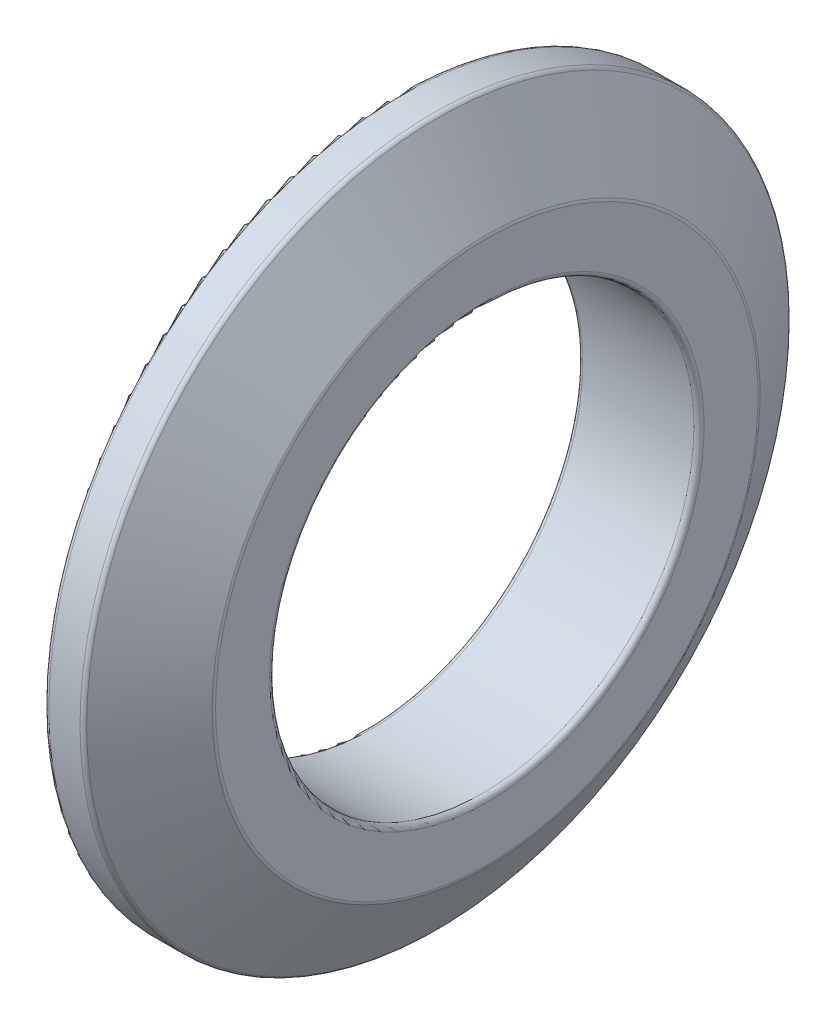
SolidWorks part; units mm, degrees
ref_plane "Front Plane" through (0, 0, 0) normal (0, 0, 1) x (1, 0, 0)
ref_plane "Top Plane" through (0, 0, 0) normal (0, 1, 0) x (1, 0, 0)
ref_plane "Right Plane" through (0, 0, 0) normal (1, 0, 0) x (0, 0, -1)
sketch "Sketch1" plane through (0, 0, 0) normal (0, 0, 1) x (1, 0, 0)
  line L0 (6, 10.75) -> (6, 13.4283)
  line L1 (0, 0) -> (6, 0) construction
  line L2 (0, 0) -> (0, 10.5) construction
  line L3 (0, 10.5) -> (6, 10.5) construction
  line L4 (6, 0) -> (6, 10.5) construction
  line L5 (5.962, 13.5608) -> (3.5734, 17.3825)
  line L6 (3.3614, 17.5) -> (1.8236, 17.5)
  line L7 (1.5817, 17.1869) -> (2.9183, 12.0631)
  line L8 (2.6764, 11.75) -> (0.25, 11.75)
  line L9 (0, 11.5) -> (0, 10.75)
  line L10 (5.75, 10.5) -> (0.25, 10.5)
  arc A0 (0.25, 11.75) -> (0, 11.5) centre (0.25, 11.5) ccw
  arc A1 (1.8236, 17.5) -> (1.5817, 17.1869) centre (1.8236, 17.25) ccw
  arc A2 (3.5734, 17.3825) -> (3.3614, 17.5) centre (3.3614, 17.25) ccw
  arc A3 (2.9183, 12.0631) -> (2.6764, 11.75) centre (2.6764, 12) cw
  arc A4 (0, 10.75) -> (0.25, 10.5) centre (0.25, 10.75) ccw
  arc A5 (6, 10.75) -> (5.75, 10.5) centre (5.75, 10.75) cw
  arc A6 (6, 13.4283) -> (5.962, 13.5608) centre (5.75, 13.4283) ccw
  point P12 (0, 11.75)
  point P15 (1.5, 17.5)
  point P18 (3.5, 17.5)
  point P21 (3, 11.75)
  point P30 (6, 13.5)
  dimension "D9" = 0.25
  dimension "D10" = 0.25
  dimension "D1" = 6
  dimension "D2" = 10.5
  dimension "D3" = 3
  dimension "D4" = 4
  dimension "D5" = 2
  dimension "D6" = 2.5
  dimension "D7" = 1.25
  dimension "D8" = 3
revolve "Revolve1" add sketch "Sketch1" angle 360 about L1
